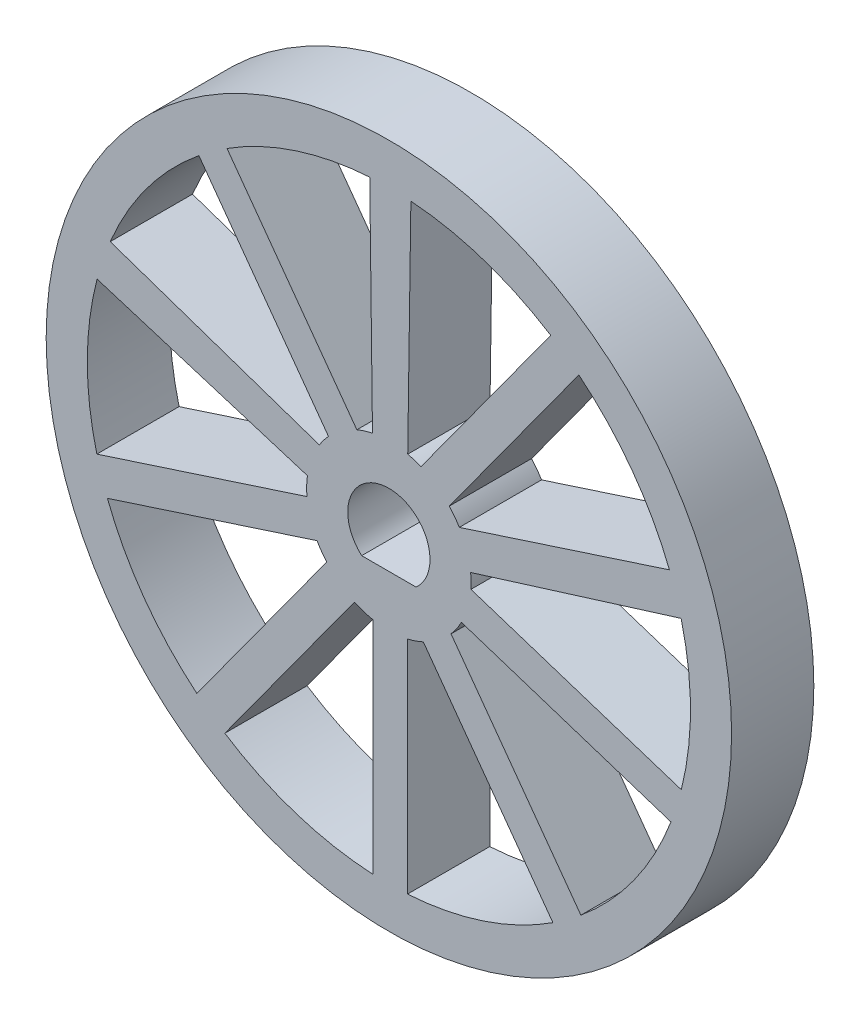
SolidWorks part; units mm, degrees
ref_plane "Front Plane" through (0, 0, 0) normal (0, 0, 1) x (1, 0, 0)
ref_plane "Top Plane" through (0, 0, 0) normal (0, 1, 0) x (1, 0, 0)
ref_plane "Right Plane" through (0, 0, 0) normal (1, 0, 0) x (0, 0, -1)
sketch "Sketch1" plane through (0, 0, 0) normal (0, 0, 1) x (1, 0, 0)
  line L0 (0, 3) -> (0, -2.25) construction
  line L1 (-4.5344, -3.9293) -> (-14.0059, -16.9657)
  line L2 (-2.5136, -5.4481) -> (-11.9675, -18.4602)
  line L4 (-1.9843, -2.25) -> (1.9843, -2.25)
  line L5 (2.5132, -5.4483) -> (11.9671, -18.4605)
  line L6 (-21.3031, -5.4935) -> (-5.9779, -0.514)
  line L8 (-1.1688, -21.9689) -> (-1.1688, -5.8851)
  line L10 (1.3588, -21.958) -> (1.3588, -5.8441)
  line L11 (4.5341, -3.9296) -> (14.0056, -16.966)
  line L14 (-20.5324, -7.9007) -> (-5.2356, -2.9305)
  line L16 (-11.8076, 18.5629) -> (-2.3362, 5.5265)
  line L18 (-13.8589, 17.086) -> (-4.405, 4.0738)
  line L20 (13.8586, 17.0863) -> (4.4047, 4.0741)
  line L22 (11.8073, 18.5631) -> (2.3358, 5.5267)
  line L24 (20.5744, -7.7907) -> (5.2931, -2.8255)
  line L26 (21.3322, -5.3793) -> (5.9871, -0.3933)
  line L32 (5.9633, 0.6622) -> (21.3172, 5.4384)
  line L34 (5.1384, 3.0979) -> (20.4635, 8.0773)
  line L37 (1.3756, 5.8402) -> (1.6048, 21.9414)
  line L38 (-1.1959, 5.8796) -> (-1.3952, 21.9557)
  line L41 (-5.0749, 3.2009) -> (-20.3269, 8.4153)
  line L42 (-5.943, 0.8253) -> (-21.2828, 5.5715)
  circle A0 centre (0, 0) radius 25
  arc A1 (1.9843, -2.25) -> (-1.9843, -2.25) centre (0, 0) ccw
  arc A2 (-5.943, 0.8253) -> (-5.9779, -0.514) centre (0, 0) ccw
  arc A3 (-13.8589, 17.086) -> (-20.3269, 8.4153) centre (0, 0) ccw
  arc A4 (-1.3952, 21.9557) -> (-11.8076, 18.5629) centre (0, 0) ccw
  arc A5 (11.8073, 18.5631) -> (1.6048, 21.9414) centre (0, 0) ccw
  arc A6 (20.4635, 8.0773) -> (13.8586, 17.0863) centre (0, 0) ccw
  arc A7 (21.3322, -5.3793) -> (21.3172, 5.4384) centre (0, 0) ccw
  arc A8 (14.0056, -16.966) -> (20.5744, -7.7907) centre (0, 0) ccw
  arc A9 (1.3588, -21.958) -> (11.9671, -18.4605) centre (0, 0) ccw
  arc A10 (-11.9675, -18.4602) -> (-1.1688, -21.9689) centre (0, 0) ccw
  arc A11 (-20.5324, -7.9007) -> (-14.0059, -16.9657) centre (0, 0) ccw
  arc A12 (-21.2828, 5.5715) -> (-21.3031, -5.4935) centre (0, 0) ccw
  arc A13 (-5.2356, -2.9305) -> (-4.5344, -3.9293) centre (0, 0) ccw
  arc A14 (-2.5136, -5.4481) -> (-1.1688, -5.8851) centre (0, 0) ccw
  arc A15 (1.3588, -5.8441) -> (2.5132, -5.4483) centre (0, 0) ccw
  arc A16 (4.5341, -3.9296) -> (5.2931, -2.8255) centre (0, 0) ccw
  arc A17 (5.9871, -0.3933) -> (5.9633, 0.6622) centre (0, 0) ccw
  arc A18 (5.1384, 3.0979) -> (4.4047, 4.0741) centre (0, 0) ccw
  arc A19 (2.3358, 5.5267) -> (1.3756, 5.8402) centre (0, 0) ccw
  arc A20 (-1.1959, 5.8796) -> (-2.3362, 5.5265) centre (0, 0) ccw
  arc A21 (-4.405, 4.0738) -> (-5.0749, 3.2009) centre (0, 0) ccw
  point P37 (0.0524, 0.1613)
  dimension "D1" = 50
  dimension "D2" = 6
  dimension "D3" = 3
  dimension "D4" = 3
  dimension "D5" = 3.9686
  dimension "D6" = 5
extrude "Boss-Extrude2" add sketch "Sketch1" along normal blind 6
